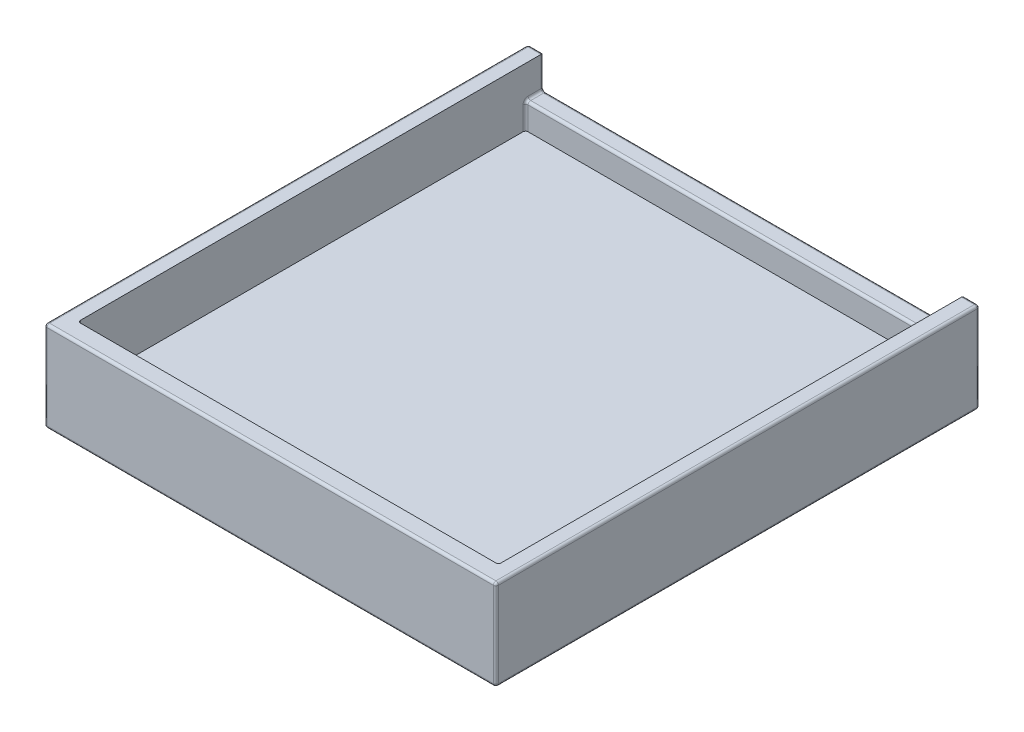
SolidWorks part; units mm, degrees
ref_plane "Front Plane" through (0, 0, 0) normal (0, 0, 1) x (1, 0, 0)
ref_plane "Top Plane" through (0, 0, 0) normal (0, 1, 0) x (1, 0, 0)
ref_plane "Right Plane" through (0, 0, 0) normal (1, 0, 0) x (0, 0, -1)
sketch "Sketch1" plane through (0, 0, 0) normal (0, 1, 0) x (1, 0, 0)
  line L1 (0, 0) -> (70, 0)
  line L2 (0, 0) -> (0, 75)
  line L3 (0, 75) -> (70, 75)
  line L4 (70, 0) -> (70, 75)
  dimension "D1" = 75
  dimension "D2" = 70
extrude "Boss-Extrude1" add sketch "Sketch1" along normal blind 9
sketch "Sketch2" plane through (0, 9, 0) normal (0, 1, 0) x (1, 0, 0)
  line L0 (35, 75) -> (35, 0) construction
  line L1 (70, 75) -> (0, 75) construction
  line L2 (0, 0) -> (70, 0) construction
  line L4 (2.4, 2.8) -> (67.6, 2.8)
  line L5 (2.4, 2.8) -> (2.4, 72.2)
  line L6 (2.4, 72.2) -> (67.6, 72.2)
  line L7 (67.6, 2.8) -> (67.6, 72.2)
  line L8 (2.4, 2.8) -> (67.6, 72.2) construction
  line L9 (2.4, 72.2) -> (67.6, 2.8) construction
  point P6 (35, 37.5)
  dimension "D1" = 69.4
  dimension "D2" = 65.2
extrude "Cut-Extrude1" cut sketch "Sketch2" against normal offset from surface (4 mm away) 5 up to face at (35, 0, -37.5)
sketch "Sketch4" plane through (0, 0, 0) normal (0, -1, 0) x (1, 0, 0)
  line L0 (35, 0) -> (35, -75) construction
  line L1 (0, 0) -> (70, 0) construction
  line L2 (70, -75) -> (0, -75) construction
  circle A0 centre (17.5, -54) radius 2.5
  circle A1 centre (52.5, -54) radius 2.5
  dimension "D1" = 5
  dimension "D2" = 35
  dimension "D3" = 54
extrude "Boss-Extrude3" add sketch "Sketch4" along normal blind 7.5
sketch "Sketch5" plane through (0, 9, 0) normal (0, 1, 0) x (1, 0, 0)
  line L1 (67.6, 2.8) -> (67.6, 72.2) construction
  line L3 (2.4, 72.2) -> (2.4, 2.8) construction
  line L4 (0, 75) -> (0, 0)
  line L5 (0, 0) -> (70, 0)
  line L6 (70, 0) -> (70, 75)
  line L7 (70, 75) -> (0, 75)
  line L8 (0, 75) -> (0, 0)
  line L9 (0, 0) -> (2.4, 0)
  line L10 (70, 0) -> (70, 75)
  line L11 (70, 75) -> (67.6, 75)
  line L13 (67.6, 2.8) -> (67.6, 72.2)
  line L15 (2.4, 72.2) -> (2.4, 2.8)
  line L16 (2.4, 72.2) -> (2.4, 75)
  line L17 (67.6, 72.2) -> (67.6, 75)
  line L18 (2.4, 2.8) -> (2.4, 0)
  line L19 (67.6, 2.8) -> (67.6, 0)
  line L20 (2.4, 75) -> (0, 75)
  line L21 (67.6, 0) -> (70, 0)
  line L22 (0, 0) -> (70, 0) construction
  line L23 (2.4, 2.8) -> (67.6, 2.8) construction
  line L24 (67.6, 72.2) -> (2.4, 72.2) construction
  line L25 (70, 75) -> (0, 75) construction
  line L26 (0, 0) -> (70, 0)
  line L27 (2.4, 2.8) -> (67.6, 2.8)
  line L28 (67.6, 72.2) -> (2.4, 72.2)
  line L29 (70, 75) -> (0, 75)
  line L30 (2.4, 2.8) -> (67.6, 2.8)
  line L31 (67.6, 72.2) -> (2.4, 72.2)
  line L32 (2.4, 75) -> (67.6, 75)
  line L33 (67.6, 0) -> (2.4, 0)
  line M12 (67.6, 2.8) -> (2.4, 2.8)
  line M14 (0, 0) -> (70, 0)
  dimension "D1" = 0
extrude "Boss-Extrude4" add sketch "Sketch5" along normal blind 5 contours L19 L18 M12 M14
fillet "Fillet1" radius 0.4 27 edges at (2.4, 9.5, -2.8) (67.6, 9.5, -2.8) (67.6, 7, -72.2) (2.4, 7, -72.2) (35, 0, 0) (70, 0, -37.5) (35, 0, -75) (35, 9, -75) (0, 0, -37.5) (0, 7, -75) (70, 7, -75) (70, 7, 0) (0, 7, 0) (52.5, 0, -51.5) (17.5, 0, -56.5) (52.5, -7.5, -51.5) (17.5, -7.5, -56.5) (68.8, 14, -75) (70, 14, -37.5) (0, 14, -37.5) (1.2, 14, -75) (2.4, 11.5, -75) (35, 14, 0) (35, 9, -72.2) (2.4, 9, -73.6) (67.6, 9, -73.6) (67.6, 11.5, -75)
